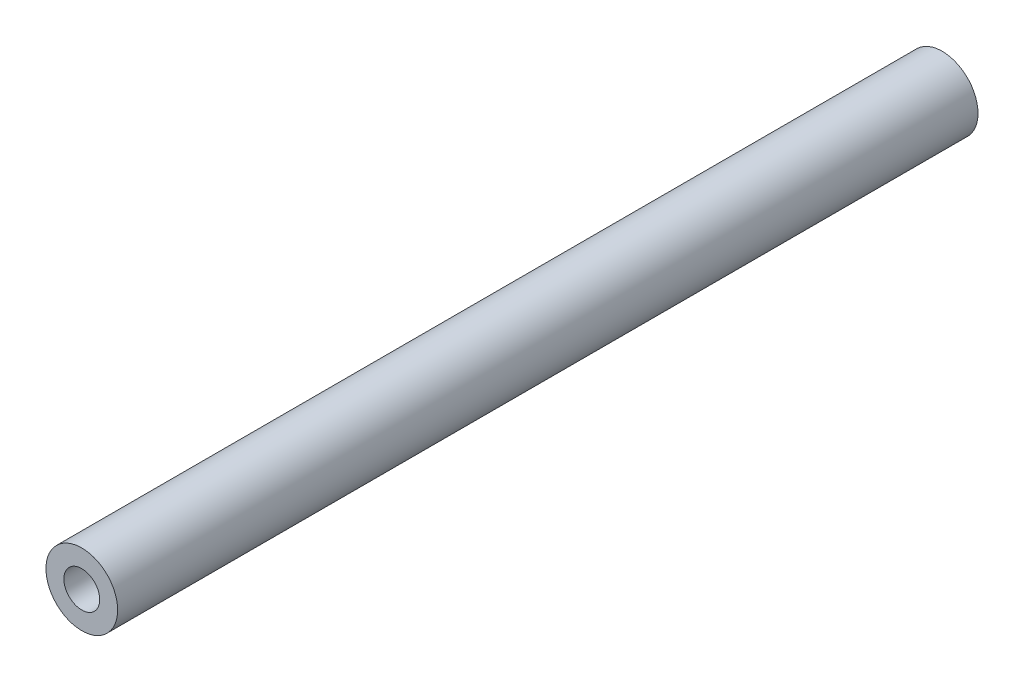
SolidWorks part; units mm, degrees
ref_plane "Front Plane" through (0, 0, 0) normal (0, 0, 1) x (1, 0, 0)
ref_plane "Top Plane" through (0, 0, 0) normal (0, 1, 0) x (1, 0, 0)
ref_plane "Right Plane" through (0, 0, 0) normal (1, 0, 0) x (0, 0, -1)
sketch "Sketch1" plane through (0, 0, 0) normal (0, 0, 1) x (1, 0, 0)
  circle A0 centre (0, 0) radius 10
  dimension "D1" = 20
extrude "Boss-Extrude1" add sketch "Sketch1" along normal mid plane 200
sketch "Sketch3" plane through (0, 0, 100) normal (0, 0, 1) x (1, 0, 0)
  circle A0 centre (0, 0) radius 5
  circle A1 centre (0, 0) radius 10
  circle A2 centre (0, 0) radius 10 construction
  dimension "D1" = 10
extrude "Boss-Extrude2" add sketch "Sketch3" along normal blind 20
mirror "Mirror1" about plane through (0, 0, 0) normal (0, 0, 1) of "Boss-Extrude2"
